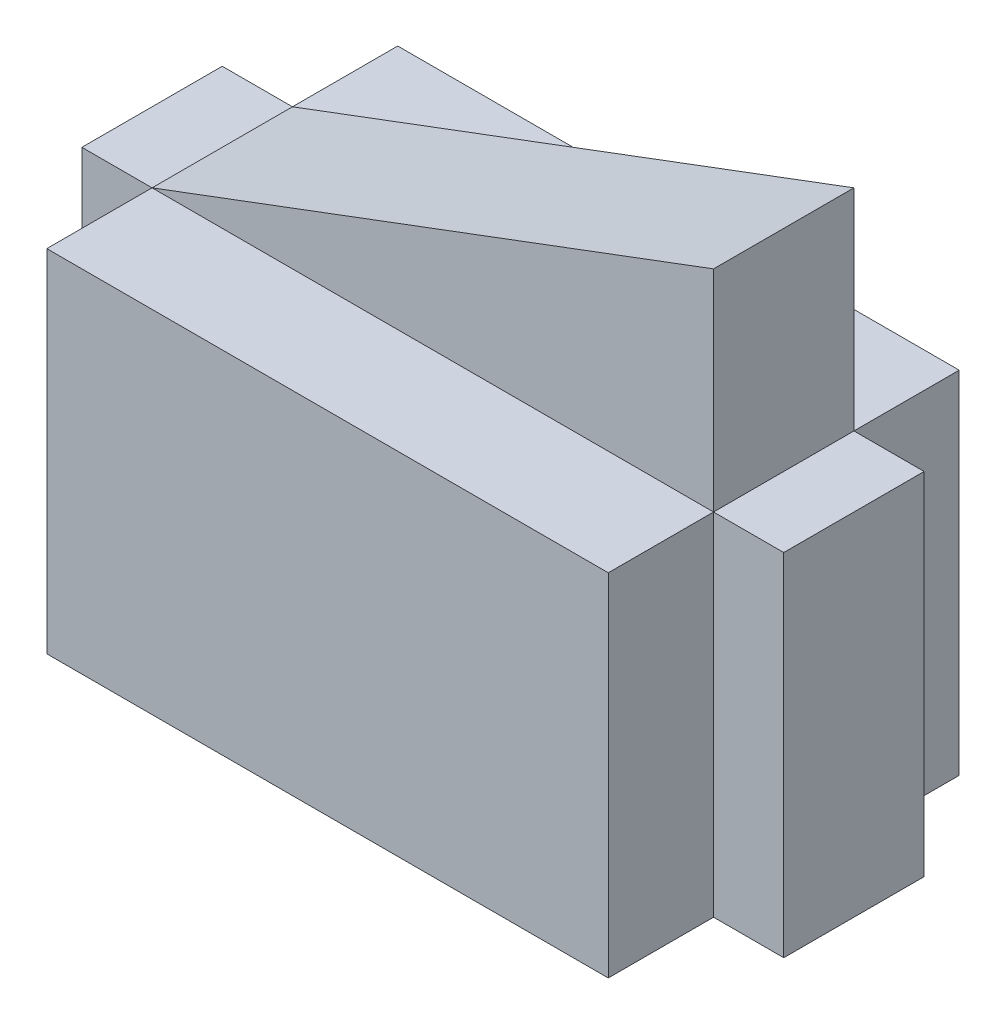
SolidWorks part; units mm, degrees
ref_plane "前视基准面" through (0, 0, 0) normal (0, 0, 1) x (1, 0, 0)
ref_plane "上视基准面" through (0, 0, 0) normal (0, 1, 0) x (1, 0, 0)
ref_plane "右视基准面" through (0, 0, 0) normal (1, 0, 0) x (0, 0, -1)
sketch "草图1" plane through (0, 0, 0) normal (0, 0, 1) x (1, 0, 0)
  line L0 (0, 8.7317) -> (0, -7.8211) construction
  line L2 (-4, 5) -> (4, 5)
  line L3 (-4, 5) -> (-4, 0)
  line L4 (-4, 0) -> (4, 0)
  line L5 (4, 5) -> (4, 0)
  dimension "D1" = 8
  dimension "D2" = 5
  dimension "D3" = 4
  dimension "D4" = 0
extrude "凸台-拉伸1" add sketch "草图1" along normal blind 5
sketch "草图2" plane through (0, 5, 0) normal (0, 1, 0) x (1, 0, 0)
  line L0 (-5.718, -2.5) -> (6.0503, -2.5) construction
  line L1 (-4, -5) -> (-4, 0) construction
  line L2 (-4, -1.5) -> (-5, -1.5)
  line L3 (-4, -1.5) -> (-4, -3.5)
  line L4 (-4, -3.5) -> (-5, -3.5)
  line L5 (-5, -1.5) -> (-5, -3.5)
  line L6 (4, -5) -> (4, 0) construction
  line L7 (4, -1.5) -> (5, -1.5)
  line L8 (4, -1.5) -> (4, -3.5)
  line L9 (4, -3.5) -> (5, -3.5)
  line L10 (5, -1.5) -> (5, -3.5)
  dimension "D1" = 1
  dimension "D2" = 1
  dimension "D3" = 2
  dimension "D4" = 1
  dimension "D5" = 1
  dimension "D6" = 1
extrude "凸台-拉伸2" add sketch "草图2" against normal up to surface (5 mm away) up to face at (0, 0, 2.5)
ref_plane "基准面5" through (0, 0, 2.5) normal (0, 0, 1) x (1, 0, 0)
sketch "草图6" plane through (0, 0, 2.5) normal (0, 0, 1) x (1, 0, 0)
  line L0 (4, 5) -> (4, 8)
  line L1 (4, 8) -> (-4, 5)
  line L2 (4, 5) -> (-4, 5) construction
  line L3 (4, 0) -> (4, 5) construction
  line L4 (4, 5) -> (4, 6.9808) construction
  line L5 (-4, 5) -> (4, 5)
  dimension "D1" = 0
  dimension "D2" = 3
extrude "凸台-拉伸3" add sketch "草图6" along normal mid plane 2
sketch "草图7" plane through (0, 5, 0) normal (0, 1, 0) x (1, 0, 0)
  line L1 (-4, 0) -> (4, 0)
  line L2 (-4, 0) -> (-4, -1.5)
  line L3 (-4, -1.5) -> (4, -1.5)
  line L4 (4, 0) -> (4, -1.5)
  line L5 (-4, -3.5) -> (4, -3.5)
  line L6 (-4, -3.5) -> (-4, -5)
  line L7 (-4, -5) -> (4, -5)
  line L8 (4, -3.5) -> (4, -5)
extrude "凸台-拉伸4" add sketch "草图7" along normal blind 1
sketch "草图8" plane through (0, 0, 5) normal (0, 0, 1) x (1, 0, 0)
  line L0 (-4, 5) -> (4, 8)
  line L1 (4, 8) -> (-4.1432, 8)
  line L2 (-4.1432, 8) -> (-4.1432, 5)
  line L3 (-5, 5) -> (-4, 5) construction
  line L4 (-4.1432, 5) -> (-4, 5)
extrude "切除-拉伸2" cut sketch "草图8" against normal through all
sketch "草图9" plane through (0, 0, 1.5) normal (0, 0, -1) x (-1, 0, 0)
  line L0 (-4, 8) -> (-4, 5)
  line L1 (-4, 5) -> (4, 5)
  line L2 (4, 5) -> (-4, 8)
extrude "切除-拉伸3" cut sketch "草图9" along normal blind 10
sketch "草图10" plane through (0, 0, 3.5) normal (0, 0, 1) x (1, 0, 0)
  line L0 (4, 8) -> (4, 5)
  line L1 (4, 5) -> (-4, 5)
  line L2 (-4, 5) -> (4, 8)
extrude "切除-拉伸4" cut sketch "草图10" along normal blind 10
sketch "草图11" plane through (0, 0, 0) normal (0, -1, 0) x (1, 0, 0)
  circle A0 centre (0, 2.5) radius 1.25
  dimension "D1" = 2.5
extrude "切除-拉伸5" cut sketch "草图11" against normal blind 1
